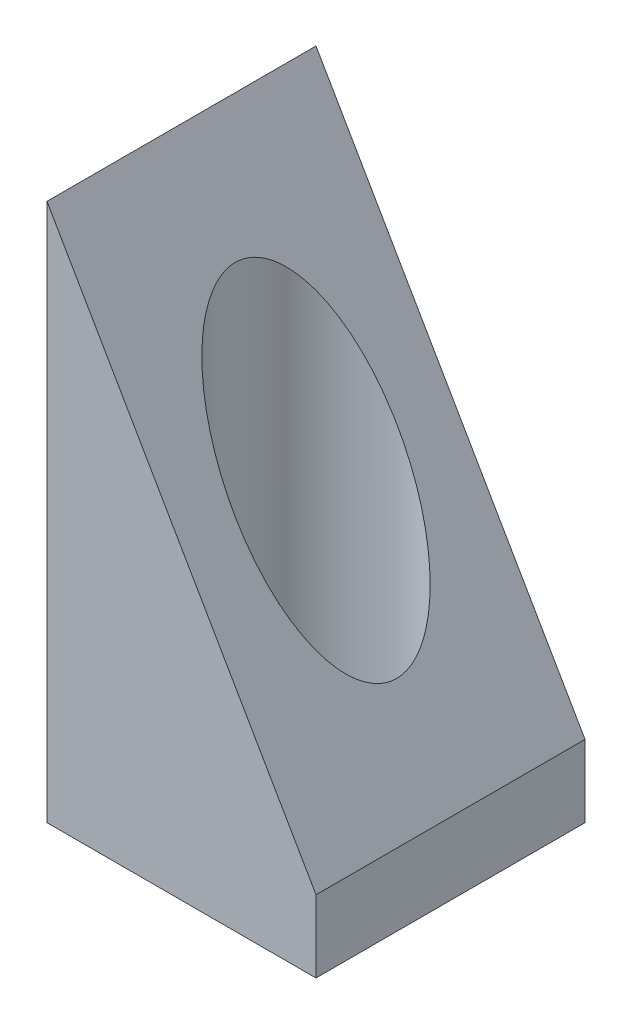
SolidWorks part; units mm, degrees
ref_plane "前基準面" through (0, 0, 0) normal (0, 0, 1) x (1, 0, 0)
ref_plane "上基準面" through (0, 0, 0) normal (0, 1, 0) x (1, 0, 0)
ref_plane "右基準面" through (0, 0, 0) normal (1, 0, 0) x (0, 0, -1)
sketch "草圖1" plane through (0, 0, 0) normal (0, 1, 0) x (1, 0, 0)
  line L1 (-20, -20) -> (20, -20)
  line L2 (-20, -20) -> (-20, 20)
  line L3 (-20, 20) -> (20, 20)
  line L4 (20, -20) -> (20, 20)
  line L5 (-20, -20) -> (20, 20) construction
  line L6 (-20, 20) -> (20, -20) construction
  circle A0 centre (0, 0) radius 12
  point P0 (0, 0)
  dimension "D3" = 24
  dimension "D1" = 40
  dimension "D2" = 40
extrude "填料-伸長1" add sketch "草圖1" along normal blind 80
sketch "草圖2" plane through (0, 0, 0) normal (0, 0, 1) x (1, 0, 0)
  line L0 (20, 10.718) -> (-20, 80)
  line L1 (20, 80) -> (20, 0) construction
  line L2 (-20, 80) -> (-20, 0) construction
  dimension "D1" = 30
extrude "除料-伸長2" cut sketch "草圖2" against normal through all and the other way through all flip side to cut
